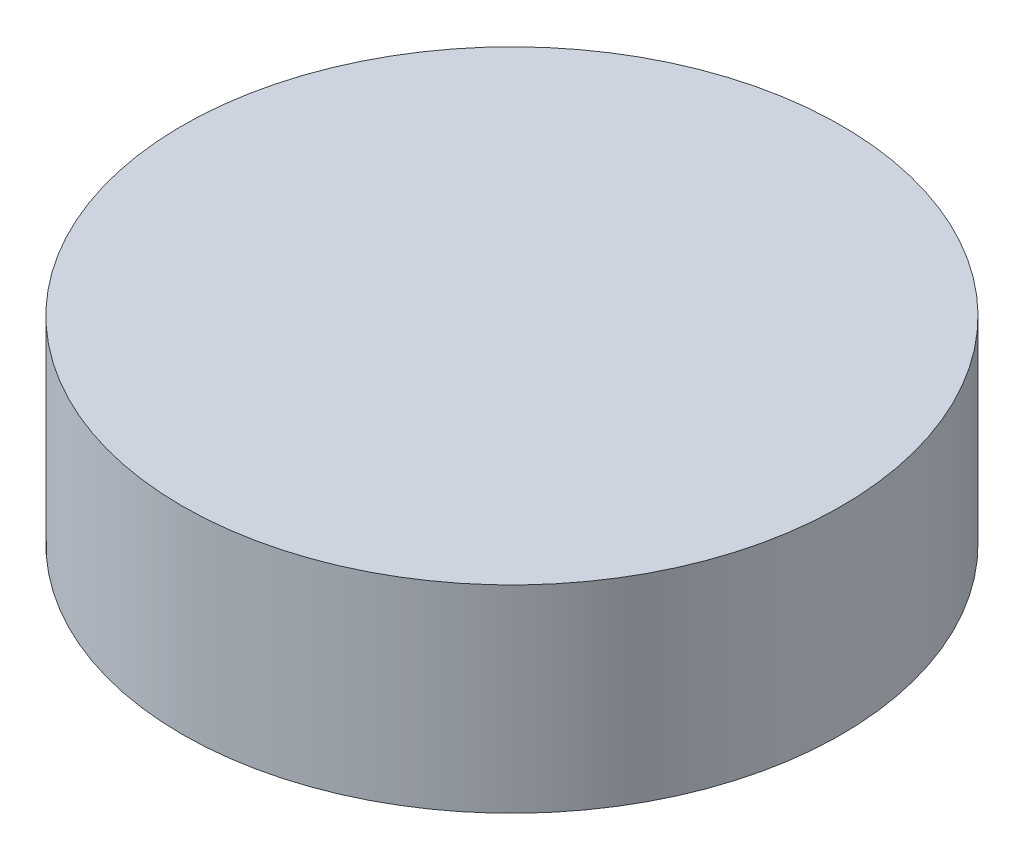
SolidWorks part; units mm, degrees
material "Alloy Steel"
ref_plane "Front Plane" through (0, 0, 0) normal (0, 0, 1) x (1, 0, 0)
ref_plane "Top Plane" through (0, 0, 0) normal (0, 1, 0) x (1, 0, 0)
ref_plane "Right Plane" through (0, 0, 0) normal (1, 0, 0) x (0, 0, -1)
sketch "Sketch1" plane through (0, 0, 0) normal (0, 1, 0) x (1, 0, 0)
  circle A0 centre (0, 0) radius 5
  dimension "D1" = 10
extrude "Boss-Extrude1" add sketch "Sketch1" along normal blind 3
